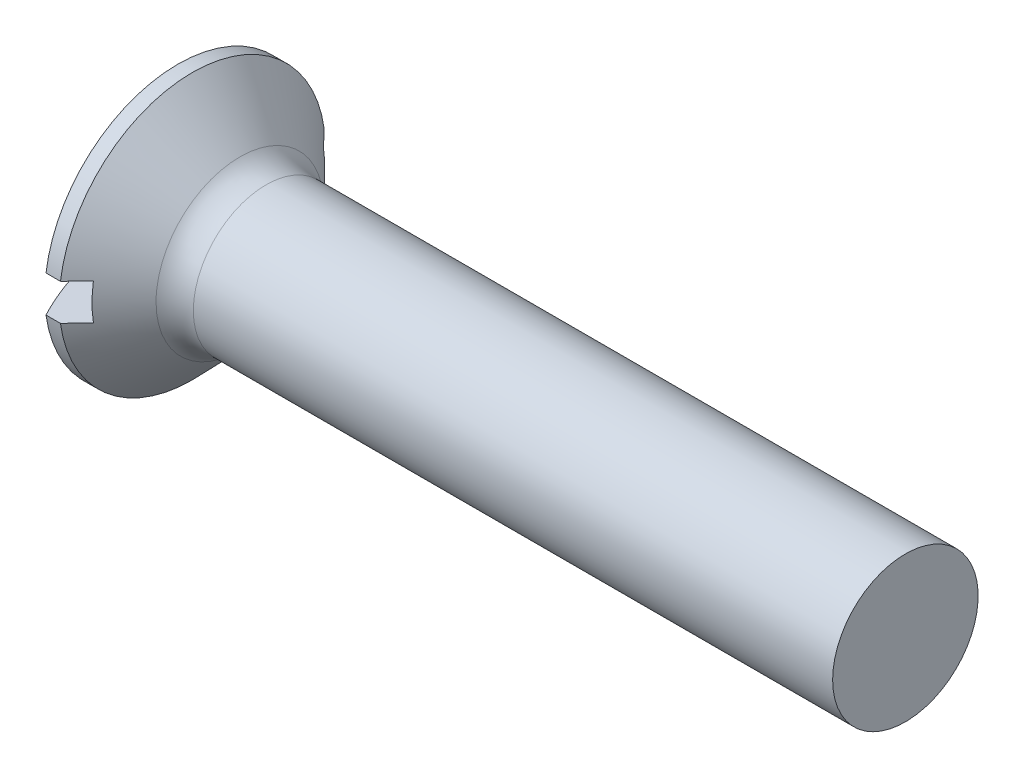
SolidWorks part; units mm, degrees
ref_plane "Plane1" through (0, 0, 0) normal (0, 0, 1) x (1, 0, 0)
ref_plane "Plane2" through (0, 0, 0) normal (0, 1, 0) x (1, 0, 0)
ref_plane "Plane3" through (0, 0, 0) normal (1, 0, 0) x (0, 0, -1)
sketch "BodySke" plane through (0, 0, 0) normal (0, 0, 1) x (1, 0, 0)
  line L0 (0, 0) -> (52.3, 0)
  line L1 (52.3, 0) -> (52.3, 5)
  line L2 (52.3, 5) -> (7.3, 5)
  line L3 (3.2924, -9.15) -> (7.3, -5) construction
  line L4 (-15.875, 0) -> (82.55, 0) construction
  line L5 (3.2924, 9.15) -> (7.3, 5)
  line L6 (8.8, 8.175) -> (8.8, -7.7) construction
  line L7 (2.3, 2.7793) -> (2.3, -13.0957) construction
  line L8 (3.2924, 9.15) -> (2.3, 9.15)
  arc A0 (0, 0) -> (2.3, 9.15) centre (19.3505, 0) cw
  dimension "Head_ang" = 92
  dimension "Diameter" = 10
  dimension "Advance" = 1.5
  dimension "Thread_nom" = 50
  dimension "Oval_ht" = 2.3
  dimension "Side_ht" = 5
  dimension "Head_dia" = 18.3
  dimension "Length" = 50
revolve "Base-Revolve" add sketch "BodySke"
cosmetic thread "ThreadCosmetic" [suppressed]
extrude "Slot" cut sketch "Sketch2" along normal blind 4.4
sketch "Sketch2" plane through (0, 0, 0) normal (1, 0, 0) x (0, 0, -1)
  line L0 (9.15, -1.25) -> (-9.15, -1.25)
  line L1 (9.15, -1.25) -> (9.15, 1.25)
  line L2 (-9.15, 1.25) -> (9.15, 1.25)
  line L3 (-9.15, 1.25) -> (-9.15, -1.25)
  dimension "D1" = 18.3
  dimension "Slot_width" = 2.5
  dimension "D3" = 9.15
  dimension "D4" = 1.25
fillet "Fillet1" radius 2.5 1 edges at (7.3, 0, 5)
sketch "ThdSchSke" plane through (0, 0, 0) normal (0, 0, 1) x (1, 0, 0)
  line L0 (8.8, -4.172) -> (8.2202, -5)
  line L1 (8.8, -4.172) -> (9.3798, -5)
  line L2 (9.3798, -5) -> (9.3798, -6.25)
  line L3 (-3.175, 0) -> (5.1513, 0) construction
  line L5 (9.3798, -6.25) -> (8.2202, -6.25)
  line L6 (8.2202, -6.25) -> (8.2202, -5)
  dimension "Diameter" = 10
  dimension "SideAngle" = 55
  dimension "VeeAngle" = 70
  dimension "Thread_minor" = 8.344
  dimension "Overcut" = 12.5
  dimension "Start" = 8.8
revolve "ThreadSchematic" [suppressed] cut sketch "ThdSchSke" angle 360 about L3
pattern_linear "ThdSchPat" [suppressed]
equation "\"D1@Sketch2\" = \"Head_dia@BodySke\""
equation "\"D3@Sketch2\" = \"D1@Sketch2\" / 2"
equation "\"D4@Sketch2\" = \"Slot_width@Sketch2\" / 2"
equation "\"Thread_length@ThreadCosmetic\" = ((sgn( (\"Length@BodySke\" - \"Advance@BodySke\" - \"Side_ht@BodySke\" ) - \"Thread_nom@BodySke\" )-1)*( (\"Length@BodySke\" - \"Advance@BodySke\" - \"Side_ht@BodySke\" ) - \"Thread_nom@BodySke\" ))/-2+ \"Thread_nom@BodySke\""
equation "\"Thread_minor@ThdSchSke\" = \"Thread_minor@ThreadCosmetic\""
equation "\"Diameter@ThdSchSke\" = \"Diameter@BodySke\""
equation "\"Overcut@ThdSchSke\" = \"Diameter@BodySke\" * 1.25"
equation "\"Start@ThdSchSke\" = \"Oval_ht@BodySke\" + \"Length@BodySke\" - \"Thread_length@ThreadCosmetic\"  '---Countersunk---"
equation "\"Num_threads@ThdSchPat\" = int( \"Thread_length@ThreadCosmetic\" / \"Advance@BodySke\" + 0.999 )  + 1"
equation "\"Advance@ThdSchPat\" = \"Thread_length@ThreadCosmetic\" /  (\"Num_threads@ThdSchPat\" - 1) 'relax it"
